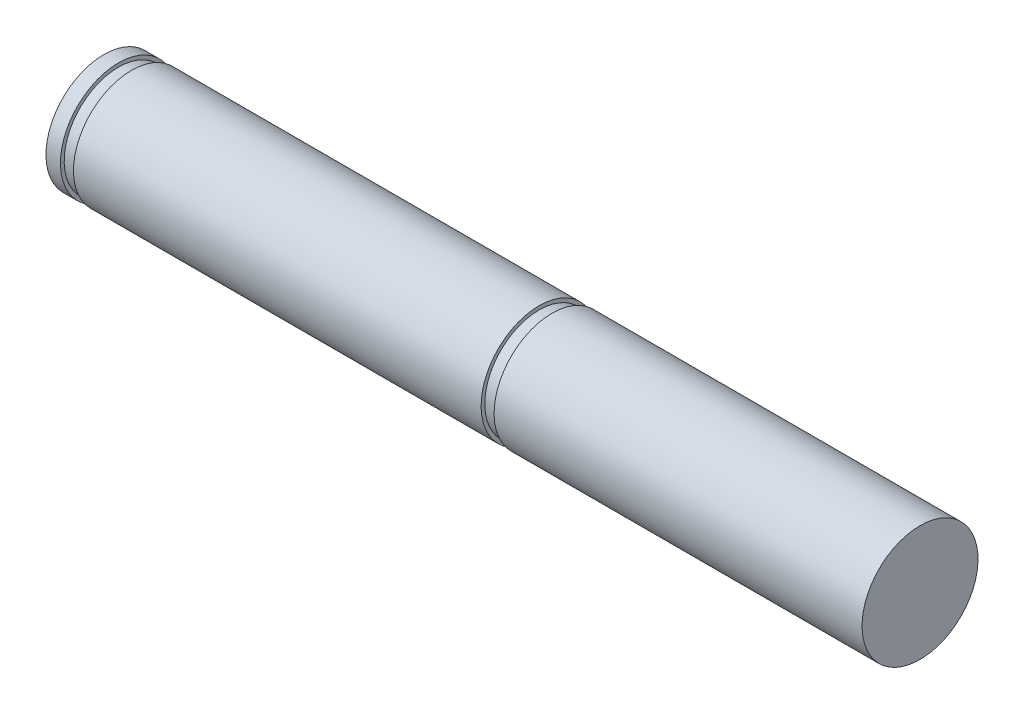
SolidWorks part; units mm, degrees
ref_plane "Front Plane" through (0, 0, 0) normal (0, 0, 1) x (1, 0, 0)
ref_plane "Top Plane" through (0, 0, 0) normal (0, 1, 0) x (1, 0, 0)
ref_plane "Right Plane" through (0, 0, 0) normal (1, 0, 0) x (0, 0, -1)
sketch "Sketch1" plane through (0, 0, 0) normal (0, 0, 1) x (1, 0, 0)
  line L0 (0, 0) -> (0, 6.35)
  line L1 (0, 6.35) -> (1.5875, 6.35)
  line L4 (89.3699, 6.35) -> (89.3699, 0)
  line L5 (89.3699, 0) -> (0, 0)
  line L6 (1.5875, 6.35) -> (1.5875, 5.9436)
  line L7 (1.5875, 5.9436) -> (3.0099, 5.9436)
  line L8 (3.0099, 5.9436) -> (3.0099, 6.35)
  line L9 (3.0099, 6.35) -> (47.6504, 6.35)
  line L10 (0, 0) -> (-5.7237, 0) construction
  line L11 (47.6504, 6.35) -> (47.6504, 5.9436)
  line L12 (47.6504, 5.9436) -> (49.0728, 5.9436)
  line L13 (49.0728, 5.9436) -> (49.0728, 6.35)
  line L14 (49.0728, 6.35) -> (89.3699, 6.35)
  point P5 (4.318, 6.35)
  dimension "D4" = 1.5875
  dimension "D7" = 1.4224
  dimension "D9" = 1.4224
  dimension "D10" = 11.8872
  dimension "D2" = 86.36
  dimension "D3" = 44.6405
  dimension "D5" = 12.7
revolve "Revolve1" add sketch "Sketch1" angle 360 about L10
equation "\"D7@Sketch1\"=\"D9@Sketch1\""
